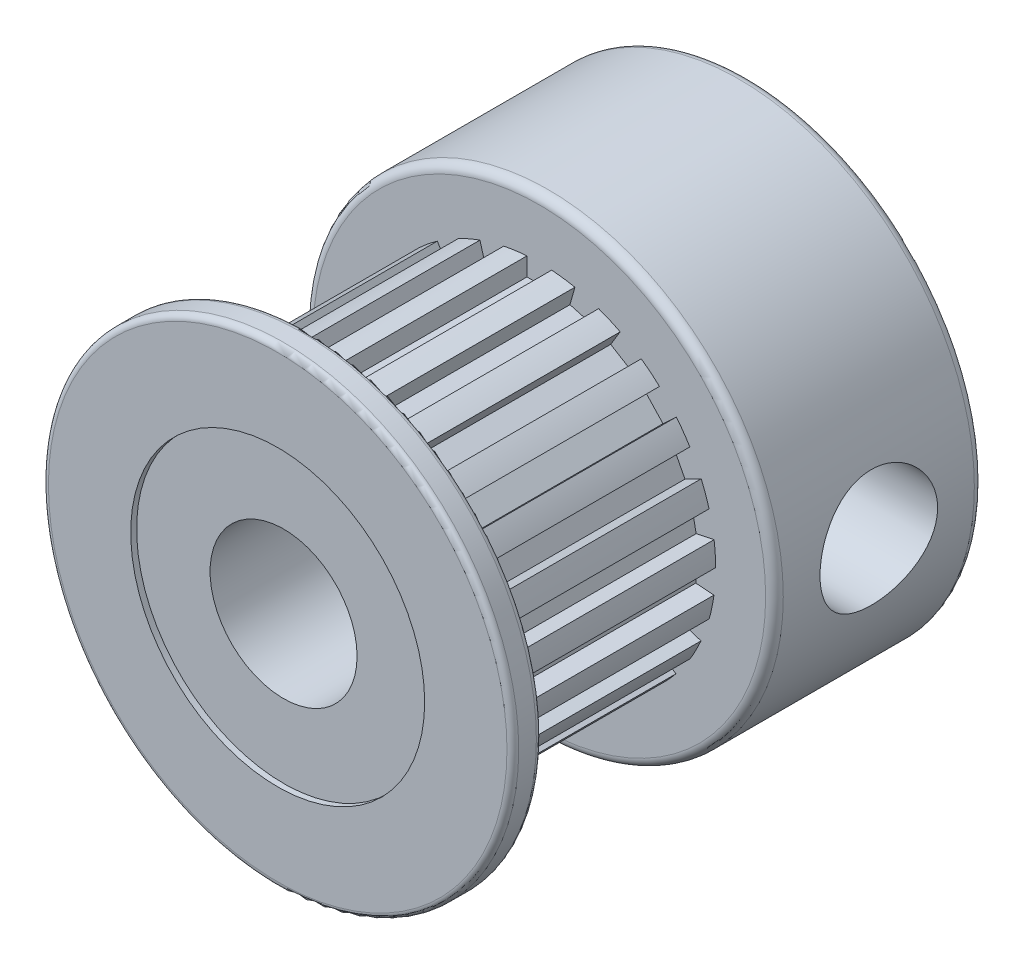
SolidWorks part; units mm, degrees
ref_plane "前视基准面" through (0, 0, 0) normal (0, 0, 1) x (1, 0, 0)
ref_plane "上视基准面" through (0, 0, 0) normal (0, 1, 0) x (1, 0, 0)
ref_plane "右视基准面" through (0, 0, 0) normal (1, 0, 0) x (0, 0, -1)
sketch "草图1" plane through (0, 0, 0) normal (0, 0, 1) x (1, 0, 0)
  circle A0 centre (0, 0) radius 8
  dimension "D1" = 16
extrude "凸台-拉伸1" add sketch "草图1" along normal blind 7.1
sketch "草图2" plane through (0, 0, 7.1) normal (0, 0, 1) x (1, 0, 0)
  circle A0 centre (0, 0) radius 6
  dimension "D1" = 12
extrude "凸台-拉伸2" add sketch "草图2" along normal blind 7.9
sketch "草图3" plane through (0, 0, 15) normal (0, 0, 1) x (1, 0, 0)
  circle A0 centre (0, 0) radius 8
  dimension "D1" = 16
extrude "凸台-拉伸3" add sketch "草图3" along normal blind 1
sketch "草图4" plane through (0, 0, 7.1) normal (0, 0, 1) x (1, 0, 0)
  line L0 (-6.0594, 0) -> (6.7938, 0) construction
  line L1 (0, 6.1) -> (0, -6.1) construction
  line L2 (1.3262, 6.2889) -> (1.0431, 5.2785)
  line L3 (-0.4197, 6.4135) -> (0.4197, 6.4135)
  line L4 (-0.4197, 6.4135) -> (-0.4197, 5.3642)
  line L5 (-0.4197, 5.3642) -> (0.4197, 5.3642)
  line L6 (0.4197, 6.4135) -> (0.4197, 5.3642)
  line L7 (-0.4197, 6.4135) -> (0.4197, 5.3642) construction
  line L8 (-0.4197, 5.3642) -> (0.4197, 6.4135) construction
  line L9 (1.3262, 6.2889) -> (2.1345, 6.0624)
  line L10 (2.1345, 6.0624) -> (1.8514, 5.0521)
  line L11 (1.0431, 5.2785) -> (1.8514, 5.0521)
  line L12 (2.9737, 5.6979) -> (2.4286, 4.8014)
  line L13 (2.9737, 5.6979) -> (3.6909, 5.2617)
  line L14 (3.6909, 5.2617) -> (3.1458, 4.3652)
  line L15 (2.4286, 4.8014) -> (3.1458, 4.3652)
  line L16 (4.4007, 4.6843) -> (3.6339, 3.9681)
  line L17 (4.4007, 4.6843) -> (4.9737, 4.0708)
  line L18 (4.9737, 4.0708) -> (4.2068, 3.3546)
  line L19 (3.6339, 3.9681) -> (4.2068, 3.3546)
  line L20 (5.5013, 3.3233) -> (4.5697, 2.8405)
  line L21 (5.5013, 3.3233) -> (5.8875, 2.578)
  line L22 (5.8875, 2.578) -> (4.9559, 2.0953)
  line L23 (4.5697, 2.8405) -> (4.9559, 2.0953)
  line L24 (6.1939, 1.7158) -> (5.1666, 1.5023)
  line L25 (6.1939, 1.7158) -> (6.3647, 0.8939)
  line L26 (6.3647, 0.8939) -> (5.3374, 0.6805)
  line L27 (5.1666, 1.5023) -> (5.3374, 0.6805)
  line L28 (6.4272, -0.019) -> (5.3804, 0.0526)
  line L29 (6.4272, -0.019) -> (6.3699, -0.8564)
  line L30 (6.3699, -0.8564) -> (5.3231, -0.7848)
  line L31 (5.3804, 0.0526) -> (5.3231, -0.7848)
  line L32 (6.1837, -1.7523) -> (5.1951, -1.4009)
  line L33 (6.1837, -1.7523) -> (5.9026, -2.5432)
  line L34 (5.9026, -2.5432) -> (4.914, -2.1918)
  line L35 (5.1951, -1.4009) -> (4.914, -2.1918)
  line L36 (5.4816, -3.3556) -> (4.6244, -2.7506)
  line L37 (5.4816, -3.3556) -> (4.9976, -4.0414)
  line L38 (4.9976, -4.0414) -> (4.1404, -3.4363)
  line L39 (4.6244, -2.7506) -> (4.1404, -3.4363)
  line L40 (4.373, -4.7101) -> (3.7109, -3.8962)
  line L41 (4.373, -4.7101) -> (3.7219, -5.2399)
  line L42 (3.7219, -5.2399) -> (3.0597, -4.426)
  line L43 (3.7109, -3.8962) -> (3.0597, -4.426)
  line L44 (2.9401, -5.7153) -> (2.5221, -4.7529)
  line L45 (2.9401, -5.7153) -> (2.1702, -6.0497)
  line L46 (2.1702, -6.0497) -> (1.7522, -5.0873)
  line L47 (2.5221, -4.7529) -> (1.7522, -5.0873)
  line L48 (1.2891, -6.2966) -> (1.1462, -5.2571)
  line L49 (1.2891, -6.2966) -> (0.4575, -6.4109)
  line L50 (0.4575, -6.4109) -> (0.3146, -5.3714)
  line L51 (1.1462, -5.2571) -> (0.3146, -5.3714)
  line L52 (-0.4575, -6.4109) -> (-0.3146, -5.3714)
  line L53 (-0.4575, -6.4109) -> (-1.2891, -6.2966)
  line L54 (-1.2891, -6.2966) -> (-1.1462, -5.2571)
  line L55 (-0.3146, -5.3714) -> (-1.1462, -5.2571)
  line L56 (-2.1702, -6.0497) -> (-1.7522, -5.0873)
  line L57 (-2.1702, -6.0497) -> (-2.9401, -5.7153)
  line L58 (-2.9401, -5.7153) -> (-2.5221, -4.7529)
  line L59 (-1.7522, -5.0873) -> (-2.5221, -4.7529)
  line L60 (-3.7219, -5.2399) -> (-3.0597, -4.426)
  line L61 (-3.7219, -5.2399) -> (-4.373, -4.7101)
  line L62 (-4.373, -4.7101) -> (-3.7109, -3.8962)
  line L63 (-3.0597, -4.426) -> (-3.7109, -3.8962)
  line L64 (-4.9976, -4.0414) -> (-4.1404, -3.4363)
  line L65 (-4.9976, -4.0414) -> (-5.4816, -3.3556)
  line L66 (-5.4816, -3.3556) -> (-4.6244, -2.7506)
  line L67 (-4.1404, -3.4363) -> (-4.6244, -2.7506)
  line L68 (-5.9026, -2.5432) -> (-4.914, -2.1918)
  line L69 (-5.9026, -2.5432) -> (-6.1837, -1.7523)
  line L70 (-6.1837, -1.7523) -> (-5.1951, -1.4009)
  line L71 (-4.914, -2.1918) -> (-5.1951, -1.4009)
  line L72 (-6.3699, -0.8564) -> (-5.3231, -0.7848)
  line L73 (-6.3699, -0.8564) -> (-6.4272, -0.019)
  line L74 (-6.4272, -0.019) -> (-5.3804, 0.0526)
  line L75 (-5.3231, -0.7848) -> (-5.3804, 0.0526)
  line L76 (-6.3647, 0.8939) -> (-5.3374, 0.6805)
  line L77 (-6.3647, 0.8939) -> (-6.1939, 1.7158)
  line L78 (-6.1939, 1.7158) -> (-5.1666, 1.5023)
  line L79 (-5.3374, 0.6805) -> (-5.1666, 1.5023)
  line L80 (-5.8875, 2.578) -> (-4.9559, 2.0953)
  line L81 (-5.8875, 2.578) -> (-5.5013, 3.3233)
  line L82 (-5.5013, 3.3233) -> (-4.5697, 2.8405)
  line L83 (-4.9559, 2.0953) -> (-4.5697, 2.8405)
  line L84 (-4.9737, 4.0708) -> (-4.2068, 3.3546)
  line L85 (-4.9737, 4.0708) -> (-4.4007, 4.6843)
  line L86 (-4.4007, 4.6843) -> (-3.6339, 3.9681)
  line L87 (-4.2068, 3.3546) -> (-3.6339, 3.9681)
  line L88 (-3.6909, 5.2617) -> (-3.1458, 4.3652)
  line L89 (-3.6909, 5.2617) -> (-2.9737, 5.6979)
  line L90 (-2.9737, 5.6979) -> (-2.4286, 4.8014)
  line L91 (-3.1458, 4.3652) -> (-2.4286, 4.8014)
  line L92 (-2.1345, 6.0624) -> (-1.8514, 5.0521)
  line L93 (-2.1345, 6.0624) -> (-1.3262, 6.2889)
  line L94 (-1.3262, 6.2889) -> (-1.0431, 5.2785)
  line L95 (-1.8514, 5.0521) -> (-1.0431, 5.2785)
  line L96 (0, 0) -> (0.4197, 5.3642) construction
  point P7 (0, 5.8889)
  dimension "D1" = 23
  dimension "D2" = 5.3806
extrude "切除-拉伸1" cut sketch "草图4" along normal up to surface (7.9 mm away) up to face at (8, 0, 15)
sketch "草图5" plane through (0, 0, 16) normal (0, 0, 1) x (1, 0, 0)
  circle A0 centre (0, 0) radius 2.5
  dimension "D1" = 5
extrude "切除-拉伸2" cut sketch "草图5" against normal blind 21
ref_plane "基准面1" through (8, 0, 0) normal (1, 0, 0) x (0, 0, -1)
sketch "草图6" plane through (8, 0, 0) normal (1, 0, 0) x (0, 0, -1)
  circle A0 centre (-3.55, 0) radius 2
  dimension "D1" = 4
extrude "切除-拉伸3" cut sketch "草图6" against normal up to surface (5.5 mm away) up to face at (2.5, 0, 16)
ref_plane "基准面2" through (0, -8, 0) normal (0, -1, 0) x (-1, 0, 0)
sketch "草图7" plane through (0, -8, 0) normal (0, -1, 0) x (-1, 0, 0)
  circle A0 centre (0, -3.55) radius 2
  dimension "D1" = 4
extrude "切除-拉伸4" cut sketch "草图7" against normal up to surface (5.5 mm away)
sketch "草图8" plane through (0, 0, 16) normal (0, 0, 1) x (1, 0, 0)
  circle A0 centre (0, 0) radius 5
extrude "切除-拉伸5" cut sketch "草图8" against normal blind 0.2
fillet "圆角1" radius 0.2 2 edges at (8, 0, 15) (8, 0, 16)
fillet "圆角2" radius 0.3 2 edges at (8, 0, 0) (8, 0, 7.1)
equation "\"7.1.00mm\"=0"
